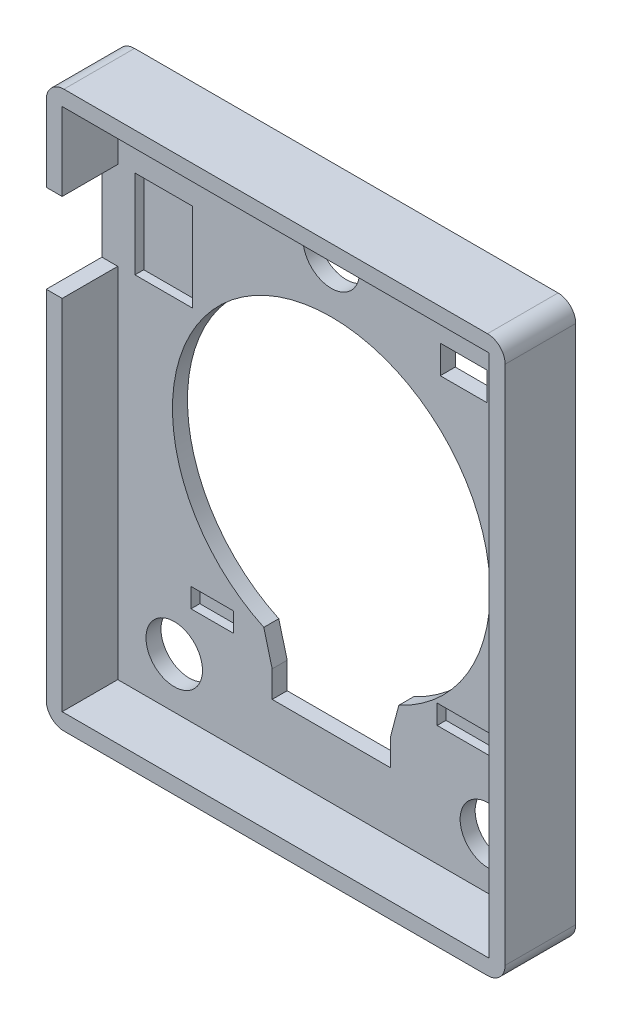
SolidWorks part; units mm, degrees
ref_plane "前视基准面" through (0, 0, 0) normal (0, 0, 1) x (1, 0, 0)
ref_plane "上视基准面" through (0, 0, 0) normal (0, 1, 0) x (1, 0, 0)
ref_plane "右视基准面" through (0, 0, 0) normal (1, 0, 0) x (0, 0, -1)
sketch "草图1" plane through (0, 0, 0) normal (0, 0, 1) x (1, 0, 0)
  line L1 (-26, -31.5) -> (26, -31.5)
  line L2 (-26, -31.5) -> (-26, 31.5)
  line L3 (-26, 31.5) -> (26, 31.5)
  line L4 (26, -31.5) -> (26, 31.5)
  line L5 (-26, -31.5) -> (26, 31.5) construction
  line L6 (-26, 31.5) -> (26, -31.5) construction
  point P0 (0, 0)
  dimension "D1" = 52
  dimension "D2" = 63
extrude "凸台-拉伸1" add sketch "草图1" along normal blind 8
sketch "草图2" plane through (0, 0, 8) normal (0, 0, 1) x (1, 0, 0)
  line L1 (-24.2, 29.7) -> (24.2, 29.7)
  line L2 (-24.2, 29.7) -> (-24.2, -29.7)
  line L3 (-24.2, -29.7) -> (24.2, -29.7)
  line L4 (24.2, 29.7) -> (24.2, -29.7)
  line L5 (-24.2, 29.7) -> (24.2, -29.7) construction
  line L6 (-24.2, -29.7) -> (24.2, 29.7) construction
  point P0 (0, 0)
  dimension "D1" = 48.4
  dimension "D2" = 59.4
extrude "切除-拉伸1" cut sketch "草图2" against normal blind 6.3
fillet "圆角1" radius 2 4 edges at (-26, -31.5, 4) (26, -31.5, 4) (26, 31.5, 4) (-26, 31.5, 4)
sketch "草图3" plane through (0, 0, 1.7) normal (0, 0, 1) x (1, 0, 0)
  line L0 (0, 9.0624) -> (0, -18.2895) construction
  line L1 (-13.1112, 0) -> (15.6963, 0) construction
  circle A0 centre (0, 24) radius 3.2
  circle A1 centre (-17.8, -24) radius 3.2
  circle A2 centre (17.8, -24) radius 3.2
  dimension "D1" = 6.4
  dimension "D2" = 6.4
  dimension "D3" = 6.4
  dimension "D4" = 24
  dimension "D5" = 17.8
  dimension "D6" = 24
extrude "切除-拉伸2" cut sketch "草图3" against normal up to next
sketch "草图4" plane through (0, 0, 1.7) normal (0, 0, 1) x (1, 0, 0)
  line L0 (-7.65, -16.2935) -> (-6.7, -19.8935)
  line L1 (-6.7, -19.8935) -> (6.7, -19.8935)
  line L2 (6.7, -19.8935) -> (7.65, -16.2935)
  line L3 (0, 6.0941) -> (0, -8.6985) construction
  line L5 (-6.7, -19.8935) -> (6.7, -19.8935)
  line L6 (-6.7, -19.8935) -> (-6.7, -22.8935)
  line L7 (-6.7, -22.8935) -> (6.7, -22.8935)
  line L8 (6.7, -19.8935) -> (6.7, -22.8935)
  line L9 (-6.7, -19.8935) -> (6.7, -22.8935) construction
  line L10 (-6.7, -22.8935) -> (6.7, -19.8935) construction
  circle A0 centre (0, 0) radius 18
  point P14 (0, -21.3935)
  dimension "D1" = 36
  dimension "D2" = 15.3
  dimension "D3" = 13.4
  dimension "D4" = 3.6
  dimension "D5" = 3
extrude "切除-拉伸3" cut sketch "草图4" against normal up to next contours A0 | A0 L0 L1 L2 | L8 L1 L6 L7
sketch "草图5" plane through (0, 0, 1.7) normal (0, 0, 1) x (1, 0, 0)
  line L1 (12.35, 21.6) -> (17.65, 21.6)
  line L2 (12.35, 21.6) -> (12.35, 18.4)
  line L3 (12.35, 18.4) -> (17.65, 18.4)
  line L4 (17.65, 21.6) -> (17.65, 18.4)
  line L5 (12.35, 21.6) -> (17.65, 18.4) construction
  line L6 (12.35, 18.4) -> (17.65, 21.6) construction
  point P4 (15, 20)
  point P5 (0, 0)
  point P7 (16.179, 20)
  dimension "D1" = 5.3
  dimension "D2" = 3.2
  dimension "D3" = 15
  dimension "D4" = 20
extrude "切除-拉伸4" cut sketch "草图5" against normal up to next
sketch "草图6" plane through (0, 0, 1.7) normal (0, 0, 1) x (1, 0, 0)
  line L1 (-20, 26.1) -> (-10, 26.1)
  line L2 (-20, 26.1) -> (-20, 23.9)
  line L3 (-20, 23.9) -> (-10, 23.9)
  line L4 (-10, 26.1) -> (-10, 23.9)
  line L5 (-20, 26.1) -> (-10, 23.9) construction
  line L6 (-20, 23.9) -> (-10, 26.1) construction
  line L7 (10, 23.9) -> (20, 23.9)
  line L8 (10, 23.9) -> (10, 26.1)
  line L9 (10, 26.1) -> (20, 26.1)
  line L10 (20, 23.9) -> (20, 26.1)
  line L11 (10, 23.9) -> (20, 26.1) construction
  line L12 (10, 26.1) -> (20, 23.9) construction
  line L13 (12, -13.9) -> (22, -13.9)
  line L14 (12, -13.9) -> (12, -16.1)
  line L15 (12, -16.1) -> (22, -16.1)
  line L16 (22, -13.9) -> (22, -16.1)
  line L17 (12, -13.9) -> (22, -16.1) construction
  line L18 (12, -16.1) -> (22, -13.9) construction
  line L19 (-15.9, -16.4) -> (-11.1, -16.4)
  line L20 (-15.9, -16.4) -> (-15.9, -18.6)
  line L21 (-15.9, -18.6) -> (-11.1, -18.6)
  line L22 (-11.1, -16.4) -> (-11.1, -18.6)
  line L23 (-15.9, -16.4) -> (-11.1, -18.6) construction
  line L24 (-15.9, -18.6) -> (-11.1, -16.4) construction
  line L25 (-22.25, 21) -> (-15.75, 21)
  line L26 (-22.25, 21) -> (-22.25, 11)
  line L27 (-22.25, 11) -> (-15.75, 11)
  line L28 (-15.75, 21) -> (-15.75, 11)
  line L29 (-22.25, 21) -> (-15.75, 11) construction
  line L30 (-22.25, 11) -> (-15.75, 21) construction
  point P0 (-15, 25)
  point P5 (15, 25)
  point P10 (17, -15)
  point P15 (-13.5, -17.5)
  point P20 (-19, 16)
  dimension "D1" = 10
  dimension "D2" = 2.2
  dimension "D3" = 10
  dimension "D4" = 2.2
  dimension "D5" = 10
  dimension "D6" = 2.2
  dimension "D7" = 4.8
  dimension "D8" = 2.2
  dimension "D9" = 15
  dimension "D10" = 15
  dimension "D11" = 25
  dimension "D12" = 25
  dimension "D13" = 15
  dimension "D14" = 17
  dimension "D15" = 13.5
  dimension "D16" = 17.5
  dimension "D17" = 6.5
  dimension "D18" = 10
  dimension "D19" = 19
  dimension "D20" = 16
extrude "切除-拉伸5" cut sketch "草图6" against normal blind 1
sketch "草图7" plane through (-24.2, 0, 0) normal (1, 0, 0) x (0, 0, -1)
  line L0 (-1.7, 29.7) -> (-1.7, -29.7) construction
  line L1 (-1.7, 20.8632) -> (-8, 20.8632)
  line L2 (-1.7, 20.8632) -> (-1.7, 10.8632)
  line L3 (-1.7, 10.8632) -> (-8, 10.8632)
  line L4 (-8, 20.8632) -> (-8, 10.8632)
  line L5 (-1.7, 20.8632) -> (-8, 10.8632) construction
  line L6 (-1.7, 10.8632) -> (-8, 20.8632) construction
  line L7 (-8, 29.7) -> (-8, -29.7) construction
  point P4 (-4.85, 15.8632)
  point P9 (0, 0)
  point P10 (-4.85, 15.8632)
  dimension "D1" = 10
extrude "切除-拉伸6" cut sketch "草图7" against normal up to next
